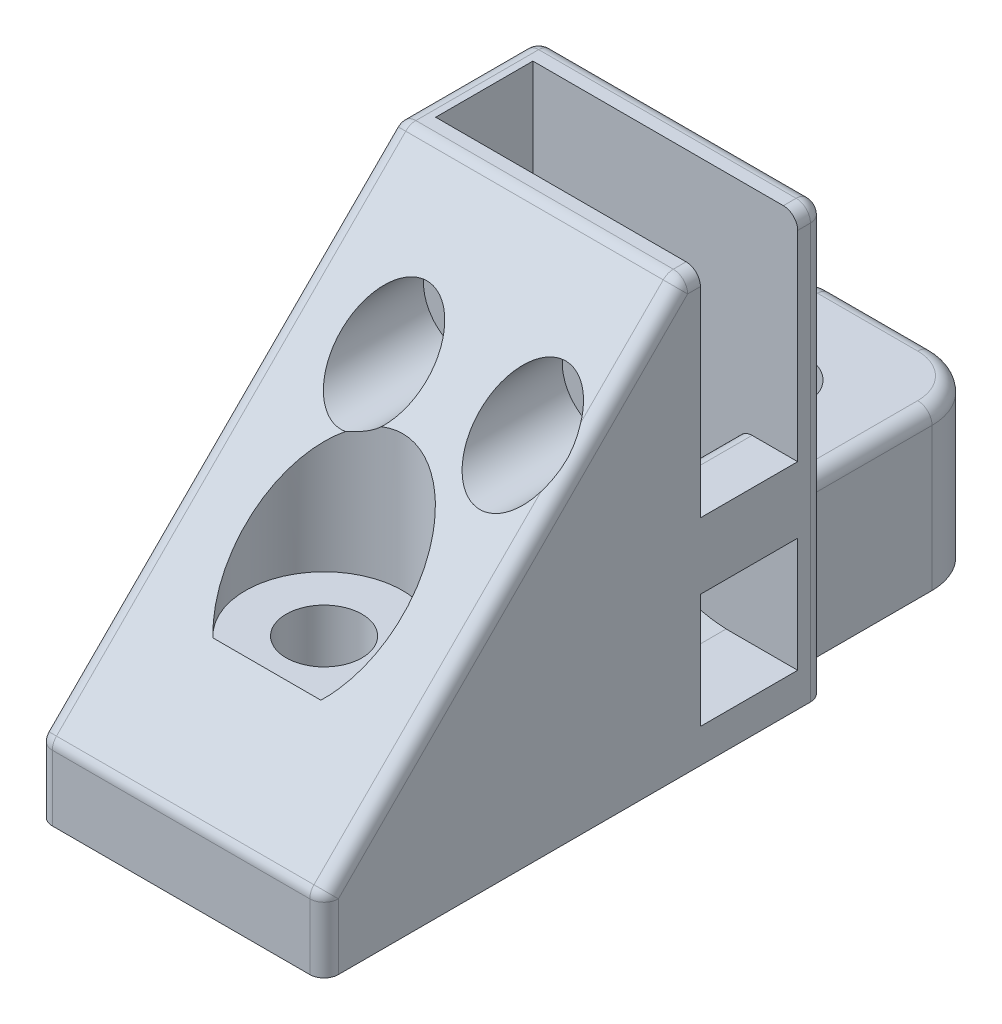
SolidWorks part; units mm, degrees
ref_plane "Front Plane" through (0, 0, 0) normal (0, 0, 1) x (1, 0, 0)
ref_plane "Top Plane" through (0, 0, 0) normal (0, 1, 0) x (1, 0, 0)
ref_plane "Right Plane" through (0, 0, 0) normal (1, 0, 0) x (0, 0, -1)
sketch "Sketch1" plane through (0, 0, 0) normal (0, 1, 0) x (1, 0, 0)
  line L1 (10, 17.5) -> (-10, 17.5)
  line L2 (10, 17.5) -> (10, -17.5)
  line L3 (10, -17.5) -> (-10, -17.5)
  line L4 (-10, 17.5) -> (-10, -17.5)
  line L5 (10, 17.5) -> (-10, -17.5) construction
  line L6 (10, -17.5) -> (-10, 17.5) construction
  point P0 (0, 0)
  dimension "D1" = 20
  dimension "D2" = 35
extrude "Boss-Extrude1" add sketch "Sketch1" along normal blind 30
chamfer "Chamfer1" distance 25 angle 45 1 edges at (0, 30, 17.5)
fillet "Fillet1" radius 1 11 edges at (0, 30, -7.5) (10, 17.5, 5) (0, 5, 17.5) (-10, 17.5, 5) (0, 30, -17.5) (-10, 15, -17.5) (10, 15, -17.5) (10, 2.5, 17.5) (-10, 2.5, 17.5) (10, 30, -12.5) (-10, 30, -12.5)
ref_plane "Plane1" through (0, 11, 0) normal (0, -1, 0) x (-1, 0, 0)
sketch "Sketch2" plane through (0, 0, 0) normal (0, -1, 0) x (-1, 0, 0)
  line L0 (9, -17.5) -> (-9, -17.5) construction
  circle A0 centre (0, -7.5) radius 2.65
  dimension "D1" = 5.3
  dimension "D2" = 10
extrude "Cut-Extrude2" cut sketch "Sketch2" against normal blind 20 contours A0
sketch "Sketch4" plane through (0, 11, 0) normal (0, -1, 0) x (-1, 0, 0)
  circle A0 centre (0, -7.5) radius 5.5
  dimension "D1" = 11
extrude "Cut-Extrude3" cut sketch "Sketch4" against normal blind 20
sketch "Sketch5" plane through (0, 30, 0) normal (0, 1, 0) x (1, 0, 0)
  line L0 (-9, 7.9142) -> (9, 7.9142) construction
  line L1 (11.542, 15.6071) -> (-8.508, 15.6071)
  line L2 (11.542, 15.6071) -> (11.542, 8.8071)
  line L3 (11.542, 8.8071) -> (-8.508, 8.8071)
  line L4 (-8.508, 15.6071) -> (-8.508, 8.8071)
  line L5 (11.542, 15.6071) -> (-8.508, 8.8071) construction
  line L6 (11.542, 8.8071) -> (-8.508, 15.6071) construction
  point P0 (1.517, 12.2071)
  dimension "D1" = 20.05
  dimension "D2" = 4.2929
  dimension "D3" = 6.8
extrude "Cut-Extrude4" cut sketch "Sketch5" against normal blind 15
sketch "Sketch6" plane through (0, 0, -8.8071) normal (0, 0, -1) x (-1, 0, 0)
  line L2 (-10, 15) -> (8.508, 15) construction
  line L4 (-10, 0) -> (-10, 29) construction
  line L5 (-10, 10.37) -> (-10, 2.37)
  line L6 (-10, 2.37) -> (-5, 2.37)
  line L8 (-5.746, 14.6642) -> (-5.746, 21.0091)
  line L9 (-5.746, 21.0091) -> (4.254, 21.0091)
  line L10 (4.254, 21.0091) -> (4.254, 12.4026)
  arc A0 (-5.746, 14.6642) -> (-10, 10.37) centre (-10.0403, 14.6642) cw
  arc A1 (-5, 2.37) -> (4.254, 12.4026) centre (-5.3893, 12.0133) ccw
  point P3 (-0.746, 19.6642)
  point P5 (-0.746, 15)
  dimension "D2" = 0
  dimension "D4" = 8
  dimension "D5" = 5
extrude "Cut-Extrude5" cut sketch "Sketch6" along normal up to vertex (6.8 mm away)
fillet "Fillet3" radius 1 2 edges at (5.746, 15, -12.2071) (-4.254, 15, -12.2071)
sketch "Sketch7" plane through (0, 0, 0) normal (0, -1, 0) x (1, 0, 0)
  line L0 (7.5, -17.5) -> (-7.5, -17.5)
  line L1 (9, -17.5) -> (-9, -17.5) construction
  line L2 (-7.5, -17.5) -> (-7.5, -27.5)
  line L3 (-3.5, -31.5) -> (3.5, -31.5)
  line L4 (7.5, -27.5) -> (7.5, -17.5)
  arc A0 (3.5, -31.5) -> (7.5, -27.5) centre (3.5, -27.5) ccw
  arc A1 (-7.5, -27.5) -> (-3.5, -31.5) centre (-3.5, -27.5) ccw
  circle A3 centre (0, -23.5) radius 2.7457
  point P5 (0, -17.5)
  point P10 (7.5, -31.5)
  point P13 (-7.5, -31.5)
  dimension "D5" = 4
  dimension "D1" = 15
  dimension "D2" = 0
  dimension "D3" = 15
  dimension "D4" = 14
  dimension "D7" = 6
extrude "Boss-Extrude2" add sketch "Sketch7" against normal blind 11
fillet "Fillet4" radius 1 5 edges at (-7.5, 11, -22.5) (7.5, 11, -22.5) (6.3284, 11, -30.3284) (0, 11, -31.5) (-6.3284, 11, -30.3284)
sketch "Sketch9" plane through (0, 11, 0) normal (0, 1, 0) x (1, 0, 0)
  line L0 (-6.5, 17.5) -> (6.5, 17.5)
  line L2 (6.5, 17.5) -> (6.5, 18)
  line L3 (6.5, 17.5) -> (6.5, 27.5) construction
  line L4 (6.5, 18) -> (-6.5, 18)
  line L5 (-6.5, 27.5) -> (-6.5, 17.5) construction
  line L6 (-6.5, 18) -> (-6.5, 17.5)
  point P6 (0, 17.5)
  dimension "D2" = 0.5
sketch "Sketch10" plane through (0, 0, -15.6071) normal (0, 0, 1) x (1, 0, 0)
  circle A0 centre (-3.358, 22.55) radius 1.65
  circle A1 centre (6.342, 22.55) radius 1.65
  point P7 (1.492, 22.55)
  dimension "D5" = 3.3
  dimension "D6" = 3.3
  dimension "D2" = 9.7
extrude "Cut-Extrude7" cut sketch "Sketch10" along normal blind 18
ref_plane "Plane2" through (0, 0, 2.1929) normal (0, 0, -1) x (-1, 0, 0)
sketch "Sketch11" plane through (0, 0, 2.1929) normal (0, 0, -1) x (-1, 0, 0)
  circle A0 centre (3.358, 22.55) radius 3
  circle A1 centre (-6.342, 22.55) radius 3
  dimension "D1" = 6
  dimension "D2" = 6
extrude "Cut-Extrude8" cut sketch "Sketch11" against normal blind 8 and the other way blind 8
